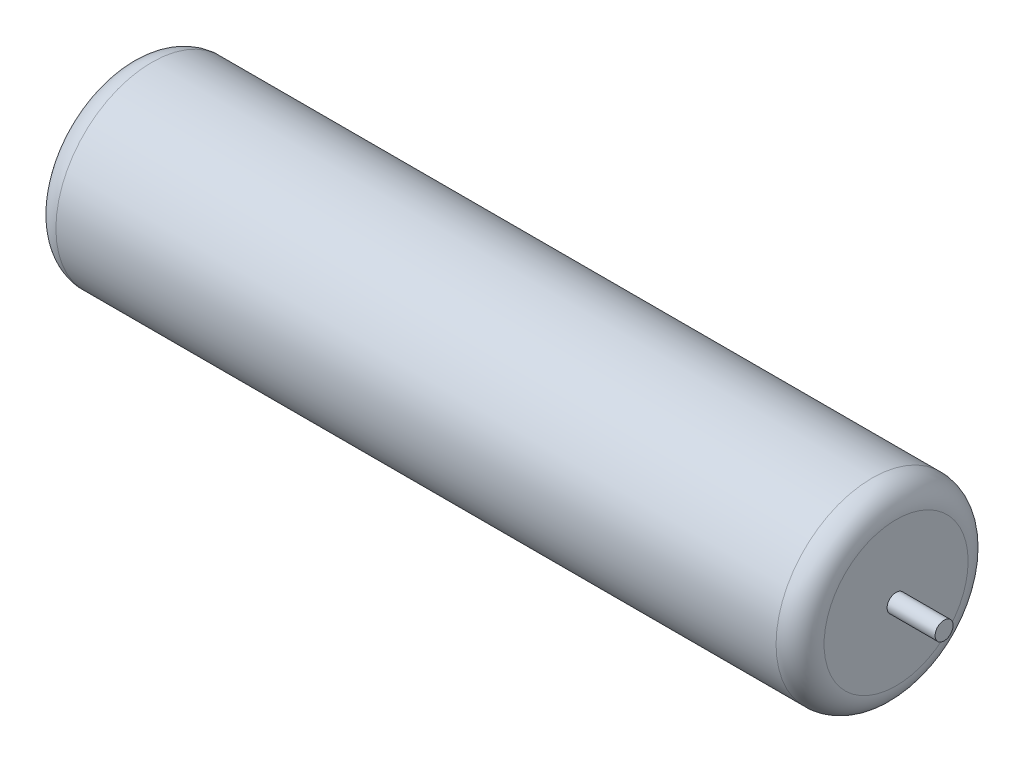
SolidWorks part; units mm, degrees
ref_plane "前视基准面" through (0, 0, 0) normal (0, 0, 1) x (1, 0, 0)
ref_plane "上视基准面" through (0, 0, 0) normal (0, 1, 0) x (1, 0, 0)
ref_plane "右视基准面" through (0, 0, 0) normal (1, 0, 0) x (0, 0, -1)
sketch "草图3" plane through (0, 0, 0) normal (1, 0, 0) x (0, 0, -1)
  circle A0 centre (0, 0) radius 4
  dimension "D1" = 8
extrude "凸台-拉伸1" add sketch "草图3" along normal blind 32
fillet "圆角1" radius 1 2 edges at (32, 0, -4) (0, 0, -4)
sketch "草图4" plane through (0, 0, 0) normal (-1, 0, 0) x (0, 0, 1)
  circle A0 centre (0, 0) radius 0.375
  dimension "D1" = 0.75
extrude "凸台-拉伸2" add sketch "草图4" along normal blind 1 and the other way blind 34
